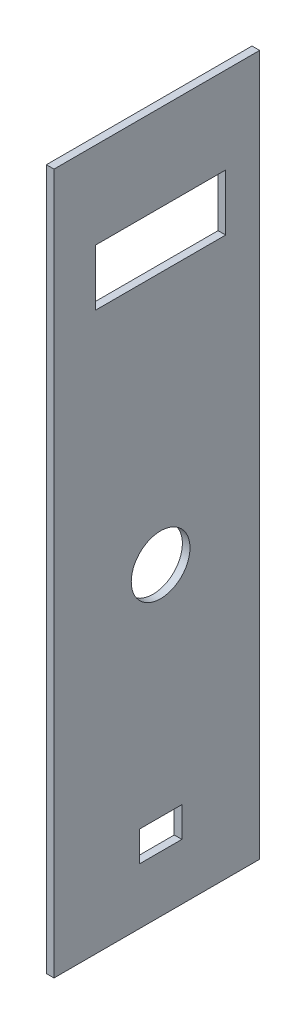
SolidWorks part; units mm, degrees
ref_plane "Front Plane" through (0, 0, 0) normal (0, 0, 1) x (1, 0, 0)
ref_plane "Top Plane" through (0, 0, 0) normal (0, 1, 0) x (1, 0, 0)
ref_plane "Right Plane" through (0, 0, 0) normal (1, 0, 0) x (0, 0, -1)
sketch "Sketch1" plane through (0, 0, 0) normal (1, 0, 0) x (0, 0, -1)
  line L1 (0, 0) -> (82.55, 0)
  line L2 (0, 0) -> (0, 292.1)
  line L3 (0, 292.1) -> (82.55, 292.1)
  line L4 (82.55, 0) -> (82.55, 292.1)
  dimension "D1" = 82.55
  dimension "D2" = 292.1
extrude "Boss-Extrude1" add sketch "Sketch1" along normal blind 3.175 contours L3 L4 L1 L2
sketch "Sketch2" plane through (0, 0, 0) normal (-1, 0, 0) x (0, 0, 1)
  line L0 (0, 292.1) -> (-82.55, 292.1) construction
  line L1 (-66.4, 234.5) -> (-16.15, 234.5)
  line L2 (-66.4, 234.5) -> (-66.4, 254)
  line L3 (-66.4, 254) -> (-16.15, 254)
  line L4 (-16.15, 234.5) -> (-16.15, 254)
  line L5 (0, 292.1) -> (-82.55, 292.1) construction
  point P8 (-41.275, 292.1)
  point P9 (-41.275, 254)
  dimension "D1" = 50.25
  dimension "D2" = 19.5
  dimension "D3" = 38.1
extrude "Cut-Extrude1" cut sketch "Sketch2" against normal up to next
ref_plane "Plane1" through (0, 0, -41.275) normal (0, 0, -1) x (-1, 0, 0)
sketch "Sketch4" plane through (0, 0, 0) normal (-1, 0, 0) x (0, 0, 1)
  line L0 (-41.275, 1.7463) -> (-41.275, -1.7462) construction
  line L2 (0, 0) -> (-82.55, 0) construction
  circle A0 centre (-41.275, 127) radius 10.25
  dimension "D1" = 20.5
  dimension "D2" = 127
extrude "Cut-Extrude2" cut sketch "Sketch4" against normal up to next
sketch "Sketch5" plane through (0, 0, 0) normal (-1, 0, 0) x (0, 0, 1)
  line L0 (-41.275, 1.7463) -> (-41.275, -1.7462) construction
  line L1 (-48.125, 33.95) -> (-34.425, 33.95)
  line L2 (-48.125, 33.95) -> (-48.125, 25.4)
  line L3 (-48.125, 25.4) -> (-34.425, 25.4)
  line L4 (-34.425, 33.95) -> (-34.425, 25.4)
  line L5 (0, 0) -> (-82.55, 0) construction
  point P4 (-41.275, 33.95)
  dimension "D1" = 8.55
  dimension "D2" = 13.7
  dimension "D3" = 25.4
extrude "Cut-Extrude3" cut sketch "Sketch5" against normal up to next
sketch "Sketch6" plane through (0, 0, 0) normal (-1, 0, 0) x (0, 0, 1)
  line L4 (-16.15, 254) -> (-66.4, 254) construction
  line L5 (-16.15, 234.5) -> (-16.15, 254) construction
  line L7 (-66.4, 234.5) -> (-16.15, 234.5) construction
  line L10 (-66.4, 254) -> (-66.4, 234.5) construction
  line L30 (-34.425, 25.4) -> (-34.425, 33.95) construction
  line L35 (-48.125, 25.4) -> (-34.425, 25.4) construction
  line L41 (-48.125, 33.95) -> (-48.125, 25.4) construction
  line L48 (-34.425, 33.95) -> (-48.125, 33.95) construction
  line L64 (-48.125, 33.95) -> (-48.125, 25.4)
  line L65 (-48.125, 25.4) -> (-34.425, 25.4)
  line L66 (-34.425, 25.4) -> (-34.425, 33.95)
  line L67 (-34.425, 33.95) -> (-48.125, 33.95)
  line L68 (-66.4, 254) -> (-66.4, 234.5)
  line L69 (-66.4, 234.5) -> (-16.15, 234.5)
  line L70 (-16.15, 234.5) -> (-16.15, 254)
  line L71 (-16.15, 254) -> (-66.4, 254)
  line L72 (-14.15, 256) -> (-68.4, 256)
  line L73 (-68.4, 256) -> (-68.4, 232.5)
  line L74 (-68.4, 232.5) -> (-14.15, 232.5)
  line L75 (-14.15, 232.5) -> (-14.15, 256)
  line L76 (-32.425, 35.95) -> (-50.125, 35.95)
  line L77 (-50.125, 35.95) -> (-50.125, 23.4)
  line L78 (-50.125, 23.4) -> (-32.425, 23.4)
  line L79 (-32.425, 23.4) -> (-32.425, 35.95)
  circle A0 centre (-41.275, 127) radius 10.25 construction
  circle A8 centre (-41.275, 127) radius 10.25
  circle A9 centre (-41.275, 127) radius 12.25
  dimension "D1" = 2
extrude "Cut-Extrude4" cut sketch "Sketch6" against normal up to next
sketch "Sketch7" plane through (3.175, 0, 0) normal (1, 0, 0) x (0, 0, -1)
  line L1 (0, 292.1) -> (-3.175, 292.1)
  line L2 (0, 292.1) -> (0, 0)
  line L3 (0, 0) -> (-3.175, 0)
  line L4 (-3.175, 292.1) -> (-3.175, 0)
extrude "Boss-Extrude2" add sketch "Sketch7" against normal blind 3.175 separate body
combine bodies "Combine1" operation type add bodies to combine 105 106
